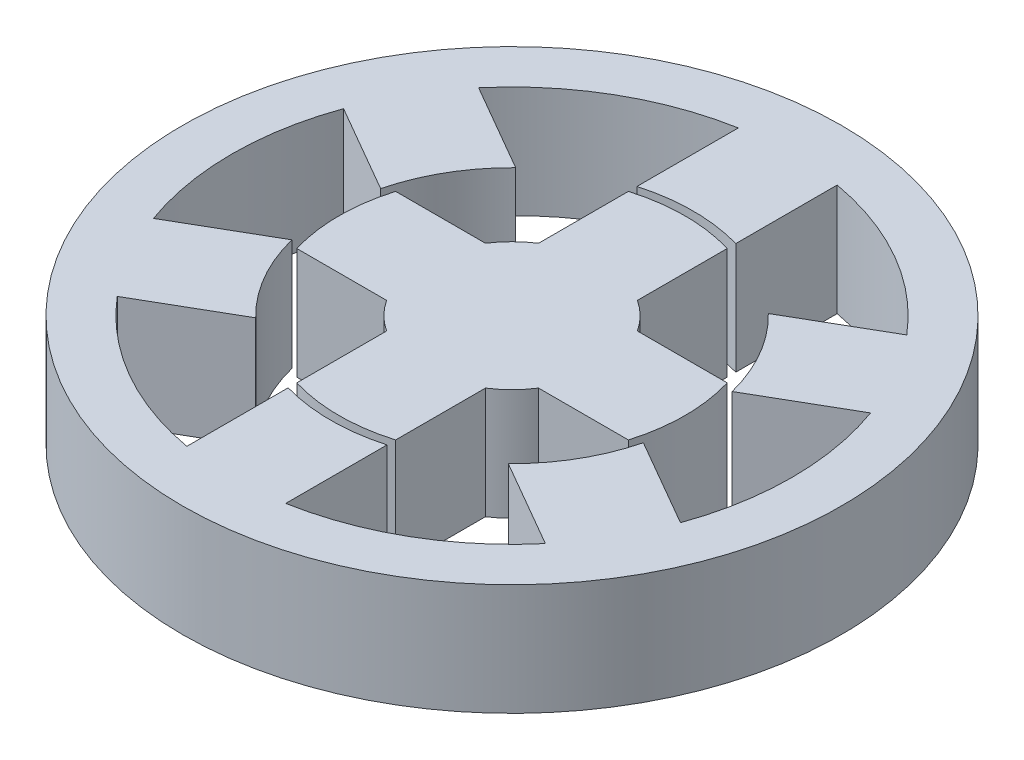
SolidWorks part; units mm, degrees
ref_plane "Ön Düzlem" through (0, 0, 0) normal (0, 0, 1) x (1, 0, 0)
ref_plane "Üst Düzlem" through (0, 0, 0) normal (0, 1, 0) x (1, 0, 0)
ref_plane "Sağ Düzlem" through (0, 0, 0) normal (1, 0, 0) x (0, 0, -1)
sketch "Çizim1" plane through (0, 0, 0) normal (0, 1, 0) x (1, 0, 0)
  line L0 (1500, 5031.1529) -> (1500, 2304.8861)
  line L1 (-1500, 5031.1529) -> (-1500, 2304.8861)
  line L2 (5031.1529, -1500) -> (2304.8861, -1500)
  line L3 (5332.5757, 1346.7132) -> (7995.6884, 2884.262)
  line L4 (1500, 5291.5026) -> (1500, 8366.6003)
  line L5 (-1500, 5291.5026) -> (-1500, 8366.6003)
  line L6 (3832.5757, 3944.7894) -> (6495.6884, 5482.3382)
  line L7 (5031.1529, 1500) -> (2304.8861, 1500)
  line L8 (3832.5757, -3944.7894) -> (6495.6884, -5482.3382)
  line L9 (-1500, -5031.1529) -> (-1500, -2304.8861)
  line L10 (5332.5757, -1346.7132) -> (7995.6884, -2884.262)
  line L11 (1500, -5031.1529) -> (1500, -2304.8861)
  line L12 (-5031.1529, 1500) -> (-2304.8861, 1500)
  line L13 (-1500, -5291.5026) -> (-1500, -8366.6003)
  line L14 (1500, -5291.5026) -> (1500, -8366.6003)
  line L15 (-5031.1529, -1500) -> (-2304.8861, -1500)
  line L16 (-5332.5757, -1346.7132) -> (-7995.6884, -2884.262)
  line L17 (-3832.5757, -3944.7894) -> (-6495.6884, -5482.3382)
  line L18 (1500, -2304.8861) -> (-1500, -2304.8861)
  line L19 (-3832.5757, 3944.7894) -> (-6495.6884, 5482.3382)
  line L20 (-5332.5757, 1346.7132) -> (-7995.6884, 2884.262)
  circle A0 centre (0, 0) radius 10000
  arc A1 (1500, -8366.6003) -> (6495.6884, -5482.3382) centre (0, 0) ccw
  arc A2 (1500, 5291.5026) -> (-1500, 5291.5026) centre (0, 0) ccw
  arc A3 (5332.5757, 1346.7132) -> (3832.5757, 3944.7894) centre (0, 0) ccw
  arc A4 (-1500, 8366.6003) -> (-6495.6884, 5482.3382) centre (0, 0) ccw
  arc A5 (-7995.6884, 2884.262) -> (-7995.6884, -2884.262) centre (0, 0) ccw
  arc A6 (5031.1529, -1500) -> (5031.1529, 1500) centre (0, 0) ccw
  arc A7 (2304.8861, 1500) -> (1500, 2304.8861) centre (0, 0) ccw
  arc A8 (-1500, 2304.8861) -> (-2304.8861, 1500) centre (0, 0) ccw
  arc A9 (-2304.8861, -1500) -> (-1500, -2304.8861) centre (0, 0) ccw
  arc A10 (3832.5757, -3944.7894) -> (5332.5757, -1346.7132) centre (0, 0) ccw
  arc A11 (6495.6884, 5482.3382) -> (1500, 8366.6003) centre (0, 0) ccw
  arc A12 (-1500, -5291.5026) -> (1500, -5291.5026) centre (0, 0) ccw
  arc A13 (-5031.1529, 1500) -> (-5031.1529, -1500) centre (0, 0) ccw
  arc A14 (-5332.5757, -1346.7132) -> (-3832.5757, -3944.7894) centre (0, 0) ccw
  arc A15 (7995.6884, -2884.262) -> (7995.6884, 2884.262) centre (0, 0) ccw
  arc A16 (-3832.5757, 3944.7894) -> (-5332.5757, 1346.7132) centre (0, 0) ccw
  arc A17 (-6495.6884, -5482.3382) -> (-1500, -8366.6003) centre (0, 0) ccw
  arc A18 (1500, 5031.1529) -> (-1500, 5031.1529) centre (0, 0) ccw
  arc A19 (-1500, -5031.1529) -> (1500, -5031.1529) centre (0, 0) ccw
  arc A20 (1500, -2304.8861) -> (2304.8861, -1500) centre (0, 0) ccw
  dimension "D1" = 6
extrude "Yükseklik-Ekstrüzyon4" add sketch "Çizim1" along normal blind 3381 contours A0 A17 L17 A14 L16 A5 L20 A16 L19 A4 L5 A2 L4 A11 L6 A3 L3 A15 L10 A10 L8 A1 L14 A12 L13 | L18 A20 L2 A6 L7 A7 L0 A18 L1 A8 L12 A13 L15 A9 | L9 A19 L11 L18
